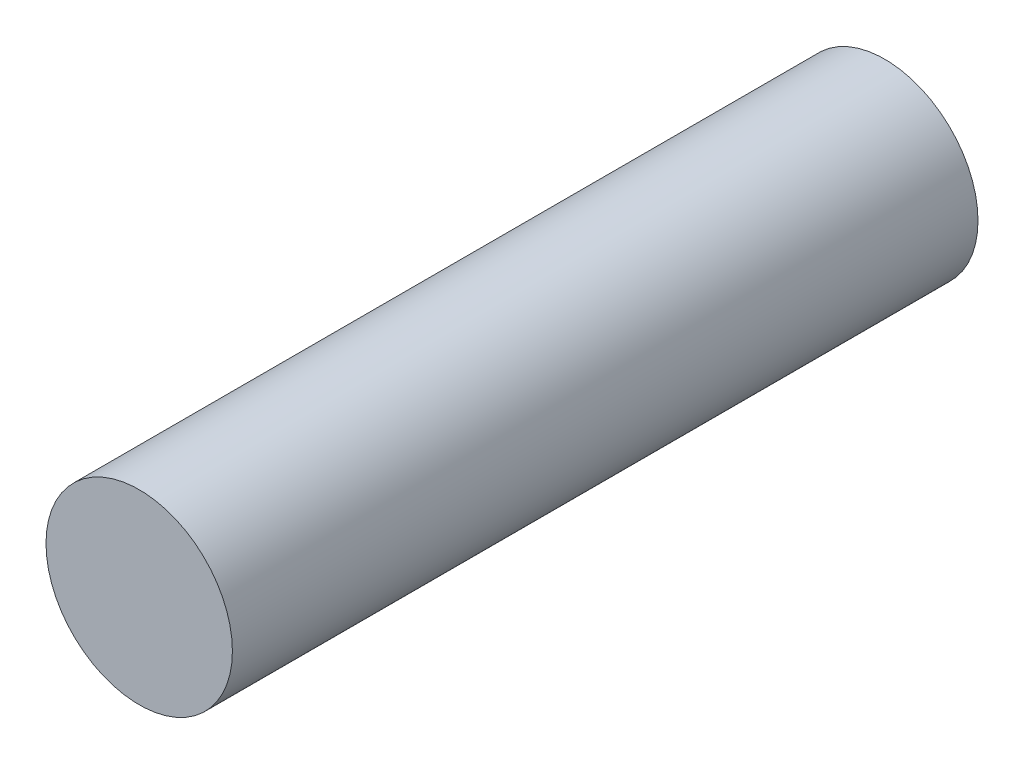
SolidWorks part; units mm, degrees
ref_plane "Front Plane" through (0, 0, 0) normal (0, 0, 1) x (1, 0, 0)
ref_plane "Top Plane" through (0, 0, 0) normal (0, 1, 0) x (1, 0, 0)
ref_plane "Right Plane" through (0, 0, 0) normal (1, 0, 0) x (0, 0, -1)
sketch "Sketch1" plane through (0, 0, 0) normal (0, 0, 1) x (1, 0, 0)
  circle A0 centre (0, 0) radius 4
  dimension "D1" = 8
extrude "Boss-Extrude1" add sketch "Sketch1" along normal blind 32
